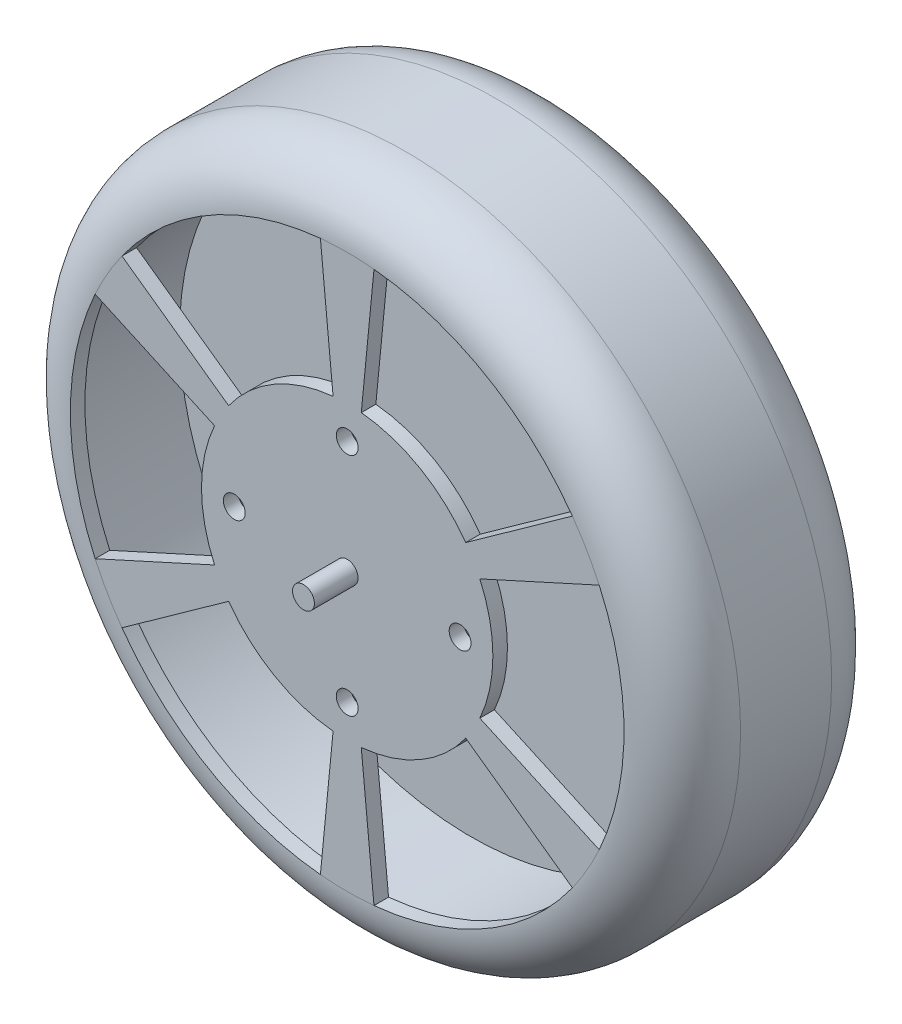
SolidWorks part; units mm, degrees
ref_plane "前视基准面" through (0, 0, 0) normal (0, 0, 1) x (1, 0, 0)
ref_plane "上视基准面" through (0, 0, 0) normal (0, 1, 0) x (1, 0, 0)
ref_plane "右视基准面" through (0, 0, 0) normal (1, 0, 0) x (0, 0, -1)
sketch "草图1" plane through (0, 0, 0) normal (0, 0, 1) x (1, 0, 0)
  circle A0 centre (0, 0) radius 20 construction
  circle A2 centre (0, 0) radius 46
  circle A3 centre (0, 0) radius 1.5 construction
  circle A4 centre (0, -20) radius 1.5 construction
  circle A5 centre (-20, 0) radius 1.5 construction
  circle A6 centre (0, 20) radius 1.5 construction
  circle A7 centre (20, 0) radius 1.5 construction
  dimension "D1" = 40
  dimension "D2" = 3
  dimension "D4" = 3
  dimension "D5" = 92
  dimension "D3" = 4
extrude "凸台-拉伸1" add sketch "草图1" along normal blind 28.5
fillet "圆角1" radius 8 2 edges at (46, 0, 0) (46, 0, 28.5)
sketch "草图2" plane through (0, 0, 28.5) normal (0, 0, 1) x (1, 0, 0)
  circle A0 centre (0, 0) radius 15.5 construction
  circle A1 centre (0, -15.5) radius 1.5
  circle A2 centre (-15.5, 0) radius 1.5
  circle A3 centre (0, 15.5) radius 1.5
  circle A4 centre (15.5, 0) radius 1.5
  dimension "D1" = 31
  dimension "D2" = 3
  dimension "D3" = 4
extrude "切除-拉伸1" cut sketch "草图2" against normal blind 4
sketch "草图3" plane through (0, 0, 28.5) normal (0, 0, 1) x (1, 0, 0)
  circle A0 centre (0, 0) radius 1.5
extrude "凸台-拉伸2" add sketch "草图3" along normal blind 6
sketch "草图5" plane through (0, 0, 0) normal (0, 0, -1) x (-1, 0, 0)
  circle A0 centre (0, 0) radius 20 construction
  circle A1 centre (-20, 0) radius 2
  circle A2 centre (0, 20) radius 2
  circle A3 centre (20, 0) radius 2
  circle A4 centre (0, -20) radius 2
  dimension "D1" = 40
  dimension "D2" = 4
  dimension "D3" = 4
extrude "切除-拉伸2" cut sketch "草图5" against normal blind 4
sketch "草图6" plane through (0, 0, 28.5) normal (0, 0, 1) x (1, 0, 0)
  line L0 (0, 0) -> (0, -38) construction
  line L1 (0, 0) -> (-3.6774, -37.8216) construction
  line L2 (-1.9355, -19.9061) -> (-3.6774, -37.8216)
  line L3 (1.9355, -19.9061) -> (3.6774, -37.8216)
  line L4 (-16.2715, -11.6292) -> (-30.9158, -22.0956)
  line L5 (-18.207, -8.2769) -> (-34.5932, -15.7261)
  line L6 (-18.207, 8.2769) -> (-34.5932, 15.7261)
  line L7 (-16.2715, 11.6292) -> (-30.9158, 22.0956)
  line L8 (-1.9355, 19.9061) -> (-3.6774, 37.8216)
  line L9 (1.9355, 19.9061) -> (3.6774, 37.8216)
  line L10 (16.2715, 11.6292) -> (30.9158, 22.0956)
  line L11 (18.207, 8.2769) -> (34.5932, 15.7261)
  line L12 (18.207, -8.2769) -> (34.5932, -15.7261)
  line L13 (16.2715, -11.6292) -> (30.9158, -22.0956)
  circle A0 centre (0, 0) radius 20 construction
  circle A1 centre (0, 0) radius 38 construction
  circle A2 centre (0, -15.5) radius 1.5 construction
  arc A3 (-18.207, -8.2769) -> (-18.207, 8.2769) centre (0, 0) cw
  arc A4 (-16.2715, -11.6292) -> (-1.9355, -19.9061) centre (0, 0) ccw
  arc A5 (1.9355, -19.9061) -> (16.2715, -11.6292) centre (0, 0) ccw
  arc A6 (18.207, -8.2769) -> (18.207, 8.2769) centre (0, 0) ccw
  arc A7 (16.2715, 11.6292) -> (1.9355, 19.9061) centre (0, 0) ccw
  arc A8 (-1.9355, 19.9061) -> (-16.2715, 11.6292) centre (0, 0) ccw
  arc A9 (-30.9158, 22.0956) -> (-3.6774, 37.8216) centre (0, 0) cw
  arc A10 (3.6774, 37.8216) -> (30.9158, 22.0956) centre (0, 0) cw
  arc A11 (34.5932, 15.7261) -> (34.5932, -15.7261) centre (0, 0) cw
  arc A12 (3.6774, -37.8216) -> (30.9158, -22.0956) centre (0, 0) ccw
  arc A13 (-30.9158, -22.0956) -> (-3.6774, -37.8216) centre (0, 0) ccw
  arc A14 (-34.5932, -15.7261) -> (-34.5932, 15.7261) centre (0, 0) cw
  dimension "D1" = 6
extrude "切除-拉伸3" cut sketch "草图6" against normal blind 12
sketch "草图7" plane through (0, 0, 0) normal (0, 1, 0) x (1, 0, 0)
  line L0 (0, -28.5) -> (0, -11.5) construction
  line L1 (-1.5, -28.5) -> (1.5, -28.5) construction
  line L2 (0, -11.5) -> (-40, -11.5)
  line L3 (-40, -11.5) -> (-40, -26.5)
  line L4 (-40, -26.5) -> (0, -26.5)
  line L5 (0, -26.5) -> (0, -11.5)
  line L6 (-3.6774, -28.5) -> (3.6774, -28.5) construction
  dimension "D1" = 40
  dimension "D2" = 15
  dimension "D3" = 2
revolve "切除-旋转1" cut sketch "草图7" angle 360 about L0
